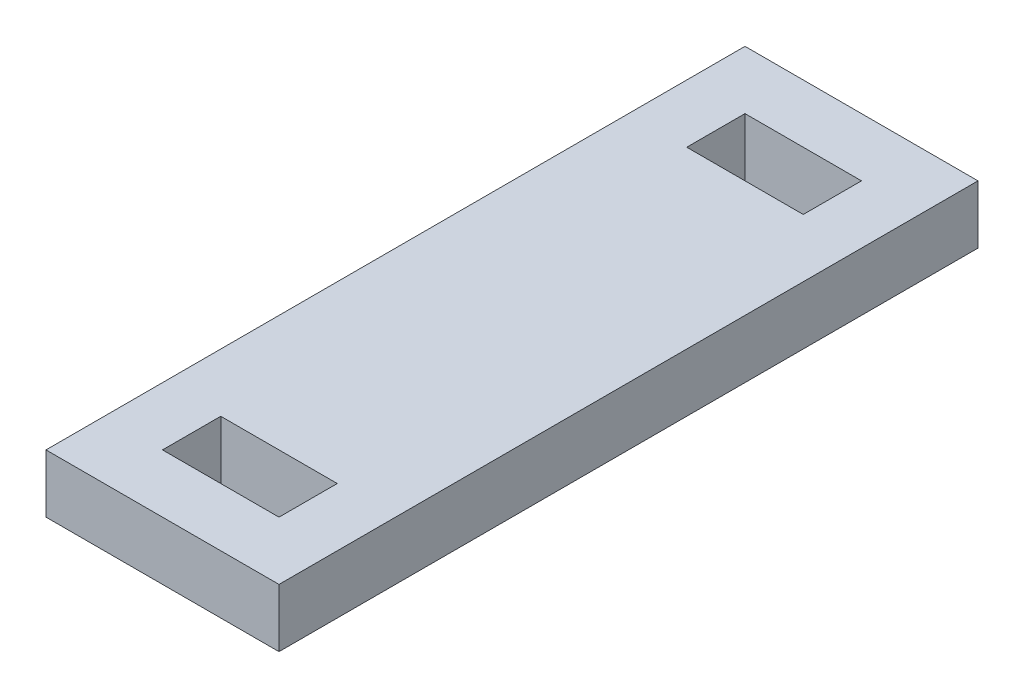
SolidWorks part; units mm, degrees
ref_plane "Front Plane" through (0, 0, 0) normal (0, 0, 1) x (1, 0, 0)
ref_plane "Top Plane" through (0, 0, 0) normal (0, 1, 0) x (1, 0, 0)
ref_plane "Right Plane" through (0, 0, 0) normal (1, 0, 0) x (0, 0, -1)
sketch "Sketch1" plane through (0, 0, 0) normal (0, 1, 0) x (1, 0, 0)
  line L1 (-13.4815, 19.4337) -> (6.5185, 19.4337)
  line L2 (-13.4815, 19.4337) -> (-13.4815, 79.4337)
  line L3 (-13.4815, 79.4337) -> (6.5185, 79.4337)
  line L4 (6.5185, 19.4337) -> (6.5185, 79.4337)
  line L5 (-8.4815, 24.4337) -> (1.5185, 24.4337)
  line L6 (-8.4815, 24.4337) -> (-8.4815, 29.4337)
  line L7 (-8.4815, 29.4337) -> (1.5185, 29.4337)
  line L8 (1.5185, 24.4337) -> (1.5185, 29.4337)
  line L9 (-8.4815, 69.4337) -> (1.5185, 69.4337)
  line L10 (-8.4815, 69.4337) -> (-8.4815, 74.4337)
  line L11 (-8.4815, 74.4337) -> (1.5185, 74.4337)
  line L12 (1.5185, 69.4337) -> (1.5185, 74.4337)
  dimension "D1" = 20
  dimension "D2" = 5
  dimension "D3" = 5
  dimension "D4" = 10
  dimension "D5" = 5
  dimension "D6" = 40
  dimension "D7" = 5
  dimension "D8" = 5
extrude "Boss-Extrude1" add sketch "Sketch1" along normal blind 5
